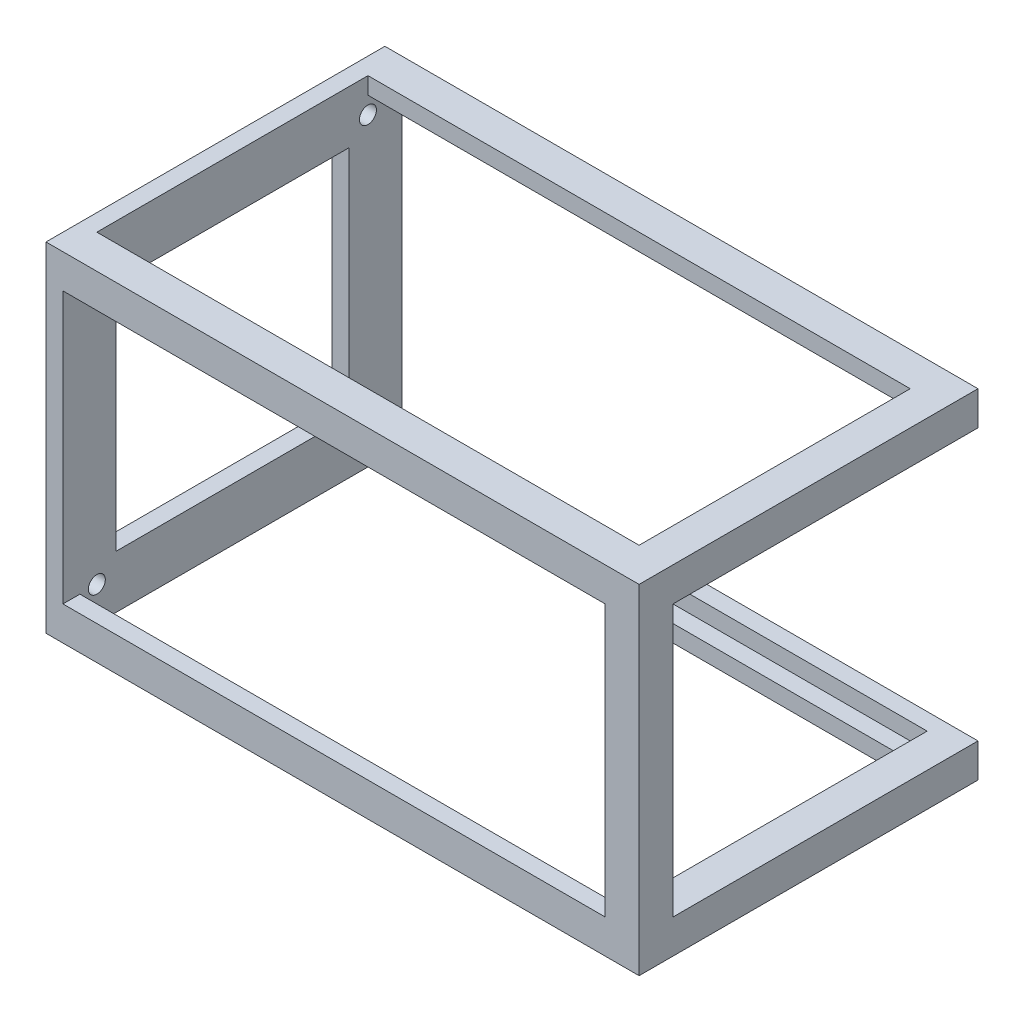
SolidWorks part; units mm, degrees
ref_plane "Alzado" through (0, 0, 0) normal (1, 0, 0) x (0, 1, 0)
ref_plane "Planta" through (0, 0, 0) normal (0, 0, 1) x (0, 1, 0)
ref_plane "Vista lateral" through (0, 0, 0) normal (0, 1, 0) x (-1, 0, 0)
sketch "Croquis1" plane through (0, 0, 0) normal (1, 0, 0) x (0, 1, 0)
  line L1 (-40, 40) -> (40, 40)
  line L2 (-40, 40) -> (-40, -40)
  line L3 (-40, -40) -> (40, -40)
  line L4 (40, 40) -> (40, -40)
  line L9 (-26, -26) -> (26, 26) construction
  line L10 (-26, 26) -> (26, -26) construction
  point P4 (0, 0)
  dimension "D1" = 80
  dimension "D2" = 80
  dimension "D3" = 40
  dimension "D4" = 40
extrude "Saliente-Extruir1" add sketch "Croquis1" along normal blind 140
sketch "Croquis7" plane through (140, 0, 0) normal (1, 0, 0) x (0, 1, 0)
  line L0 (0, 0) -> (-25.9764, 0) construction
  line L3 (-40, 32.0006) -> (-36, 32.0006)
  line L4 (-36, 36) -> (-36, 32.0006)
  line L7 (-36, 36) -> (-32, 36)
  line L8 (-32, 40) -> (-32, 36)
  line L9 (0, 0) -> (0, 18.8574) construction
  line L11 (-40, -32.0006) -> (-36, -32.0006)
  line L12 (-36, -36) -> (-36, -32.0006)
  line L13 (-36, -36) -> (-32, -36)
  line L14 (-32, -40) -> (-32, -36)
  line L19 (32, -40) -> (32, -36)
  line L20 (36, -36) -> (32, -36)
  line L21 (36, -36) -> (36, -32.0006)
  line L22 (40, -32.0006) -> (36, -32.0006)
  line L25 (40, 32.0006) -> (36, 32.0006)
  line L26 (36, 36) -> (36, 32.0006)
  line L27 (36, 36) -> (32, 36)
  line L28 (32, 40) -> (32, 36)
  line L31 (-32, -40) -> (32, -40)
  line L32 (-32, 40) -> (32, 40)
  line L33 (-40, 32.0006) -> (-40, -32.0006)
  line L35 (40, 32.0006) -> (40, -32.0006)
  dimension "D1" = 4
  dimension "D3" = 4
  dimension "D4" = 4
extrude "Cortar-Extruir3" cut sketch "Croquis7" against normal blind 136
sketch "Croquis8" plane through (4, 0, 0) normal (1, 0, 0) x (0, 1, 0)
  line L0 (-40, 32.0006) -> (-40, -32.0006) construction
  line L1 (32, 40) -> (-32, 40) construction
  line L2 (0, 0) -> (-22.1785, 0) construction
  line L3 (0, 0) -> (0, 14.3587) construction
  line L5 (-27.5, -27.5) -> (27.5, -27.5)
  line L6 (-27.5, -27.5) -> (-27.5, 27.5)
  line L7 (-27.5, 27.5) -> (27.5, 27.5)
  line L8 (27.5, -27.5) -> (27.5, 27.5)
  line L9 (-27.5, -27.5) -> (27.5, 27.5) construction
  line L10 (-27.5, 27.5) -> (27.5, -27.5) construction
  circle A0 centre (-32, 32) radius 2
  circle A1 centre (-32, -32) radius 2
  circle A2 centre (32, -32) radius 2
  circle A3 centre (32, 32) radius 2
  dimension "D1" = 4
  dimension "D2" = 8
  dimension "D3" = 8
  dimension "D4" = 55
  dimension "D5" = 55
extrude "Cortar-Extruir4" cut sketch "Croquis8" against normal blind 136
sketch "Croquis9" plane through (140, 0, 0) normal (1, 0, 0) x (0, 1, 0)
  line L0 (32, -40) -> (40, -40)
  line L1 (-40, 40) -> (40, 40)
  line L2 (-40, 40) -> (-40, -40)
  line L3 (-40, -40) -> (-32, -40)
  line L4 (40, 40) -> (40, -40)
  line L5 (-32, 32) -> (32, 32)
  line L6 (-32, 32) -> (-32, -40)
  line L8 (32, 32) -> (32, -40)
  dimension "D1" = 8
  dimension "D2" = 8
  dimension "D3" = 8
  dimension "D4" = 8
extrude "Saliente-Extruir4" add sketch "Croquis9" against normal blind 8
